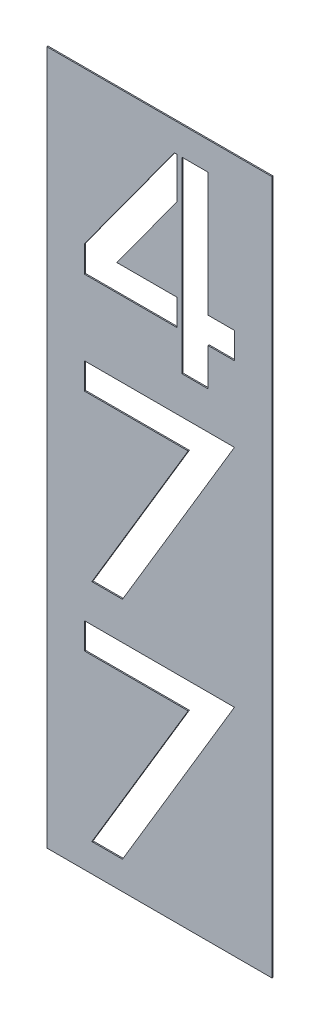
SolidWorks part; units mm, degrees
ref_plane "Front Plane" through (0, 0, 0) normal (0, 0, 1) x (1, 0, 0)
ref_plane "Top Plane" through (0, 0, 0) normal (0, 1, 0) x (1, 0, 0)
ref_plane "Right Plane" through (0, 0, 0) normal (1, 0, 0) x (0, 0, -1)
sketch "Sketch1" plane through (0, 0, 0) normal (0, 0, 1) x (1, 0, 0)
  line L0 (0, 38.5625) -> (0, -38.5625) construction
  line L1 (16.51, 76.2) -> (16.51, 34.29)
  line L4 (16.51, 34.29) -> (25.4, 34.29)
  line L7 (-25.4, 0) -> (25.4, 0)
  line L8 (25.4, 0) -> (-12.5065, -63.5)
  line L9 (-12.5065, -63.5) -> (-22.86, -63.5)
  line L10 (-22.86, -63.5) -> (9.7396, -8.89)
  line L11 (9.7396, -8.89) -> (-25.4, -8.89)
  line L12 (-25.4, -8.89) -> (-25.4, 0)
  line L13 (-4.4675, -32.6893) -> (3.1659, -37.2461) construction
  line L28 (-25.4, -76.2) -> (25.4, -76.2)
  line L29 (25.4, -76.2) -> (-12.5065, -139.7)
  line L30 (-12.5065, -139.7) -> (-22.86, -139.7)
  line L31 (25.4, 34.29) -> (25.4, 25.4)
  line L32 (25.4, 25.4) -> (16.51, 25.4)
  line L33 (16.51, 25.4) -> (16.51, 12.7)
  line L34 (16.51, 12.7) -> (7.62, 12.7)
  line L35 (7.62, 12.7) -> (7.62, 25.4)
  line L36 (7.62, 25.4) -> (-25.4, 25.4)
  line L37 (-25.4, 25.4) -> (-25.4, 34.29)
  line L38 (-25.4, 34.29) -> (5.08, 76.2)
  line L39 (5.08, 76.2) -> (16.51, 76.2)
  line L40 (7.62, 64.5779) -> (-14.4075, 34.29)
  line L41 (-14.4075, 34.29) -> (7.62, 34.29)
  line L42 (7.62, 34.29) -> (7.62, 64.5779)
  line L43 (-14.4863, 49.2963) -> (-7.2967, 44.0674) construction
  line L44 (7.62, 49.4339) -> (16.51, 49.4339) construction
  line L45 (5.08, 34.29) -> (5.08, 25.4) construction
  line L46 (0, 76.2) -> (0, -139.7) construction
  line L47 (-22.86, -139.7) -> (9.7396, -85.09)
  line L48 (-38.1, 85.725) -> (38.1, 85.725)
  line L49 (-38.1, 85.725) -> (-38.1, -149.225)
  line L50 (-38.1, -149.225) -> (38.1, -149.225)
  line L51 (38.1, 85.725) -> (38.1, -149.225)
  line L52 (-38.1, 85.725) -> (38.1, -149.225) construction
  line L53 (-38.1, -149.225) -> (38.1, 85.725) construction
  line L54 (9.7396, -85.09) -> (-25.4, -85.09)
  line L55 (-25.4, -85.09) -> (-25.4, -76.2)
  point P31 (-25.4, -94.7002)
  point P32 (-17.6832, -63.5)
  point P33 (0, 0)
  point P51 (0, 0)
  point P54 (0, -31.75)
  dimension "D2" = 8.89
  dimension "D3" = 63.5
  dimension "D4" = 63.5
  dimension "D5" = 50.8
  dimension "D6" = 25.4
  dimension "D7" = 50.8
  dimension "D8" = 8.89
  dimension "D9" = 12.7
  dimension "D17" = 2.54
  dimension "D18" = 11.43
  dimension "D19" = 25.4
  dimension "D20" = 12.7
  dimension "D21" = 8.89
  dimension "D22" = 12.7
  dimension "D23" = 76.2
  dimension "D24" = 234.95
extrude "Boss-Extrude1" add sketch "Sketch1" along normal blind 0.4
sketch "Sketch2" plane through (0, 0, 0.4) normal (0, 0, 1) x (1, 0, 0)
  line L0 (5.08, 76.2) -> (16.51, 76.2) construction
  line L1 (7.62, 25.4) -> (6.0325, 25.4)
  line L2 (7.62, 25.4) -> (7.62, 76.2)
  line L3 (7.62, 76.2) -> (6.0325, 76.2)
  line L4 (6.0325, 25.4) -> (6.0325, 76.2)
  dimension "D1" = 1.5875
extrude "Boss-Extrude2" add sketch "Sketch2" against normal up to surface (0.4 mm away) up to face at (0, -31.75, 0)
